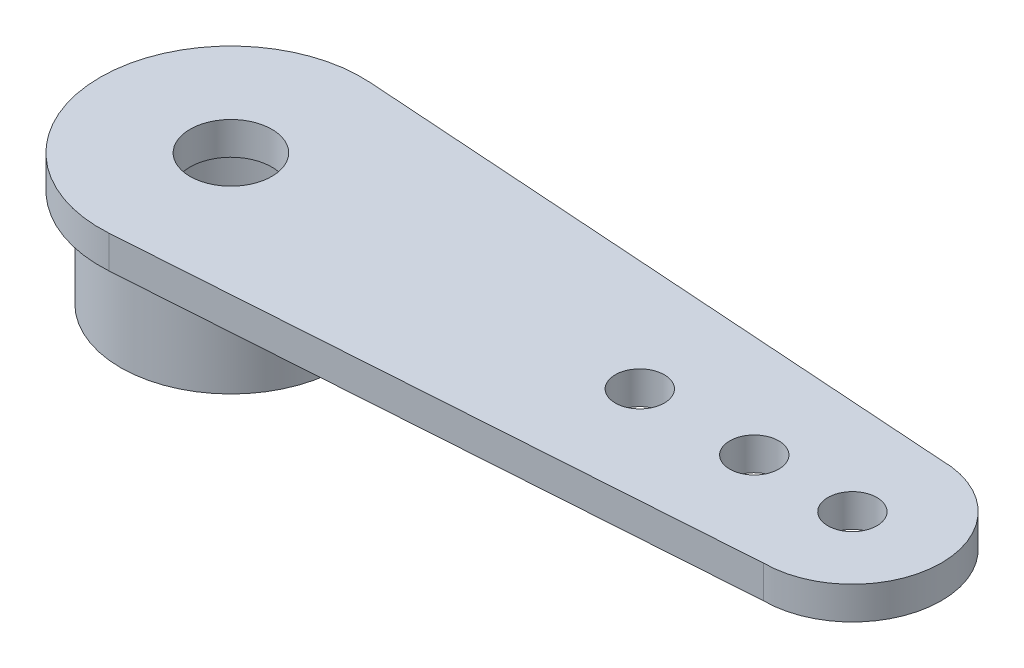
SolidWorks part; units mm, degrees
ref_plane "Front Plane" through (0, 0, 0) normal (0, 0, 1) x (1, 0, 0)
ref_plane "Top Plane" through (0, 0, 0) normal (0, 1, 0) x (1, 0, 0)
ref_plane "Right Plane" through (0, 0, 0) normal (1, 0, 0) x (0, 0, -1)
sketch "Sketch5" plane through (0, 0, 0) normal (0, 1, 0) x (1, 0, 0)
  circle A0 centre (0, 0) radius 2.794
  circle A1 centre (0, 0) radius 3.429
  dimension "D1" = 5.588
  dimension "D2" = 6.858
extrude "Boss-Extrude3" add sketch "Sketch5" along normal blind 3.048
sketch "Sketch6" plane through (0, 3.048, 0) normal (0, 1, 0) x (1, 0, 0)
  line L0 (0, 0) -> (19.304, 0)
  line L1 (19.304, 2.764) -> (0.275, 4.0547)
  line L2 (19.304, -2.764) -> (0.275, -4.0547)
  circle A0 centre (0, 0) radius 1.27
  circle A1 centre (0, 0) radius 4.064
  circle A2 centre (12.7, 0) radius 0.762
  circle A3 centre (16.256, 0) radius 0.762
  circle A4 centre (19.304, 0) radius 0.762
  circle A5 centre (19.304, 0) radius 2.764
  dimension "D1" = 2.54
  dimension "D2" = 1.524
  dimension "D3" = 1.524
  dimension "D4" = 1.524
  dimension "D5" = 8.128
  dimension "D6" = 12.7
  dimension "D7" = 16.256
  dimension "D8" = 19.304
extrude "Boss-Extrude4" add sketch "Sketch6" along normal blind 1.016
